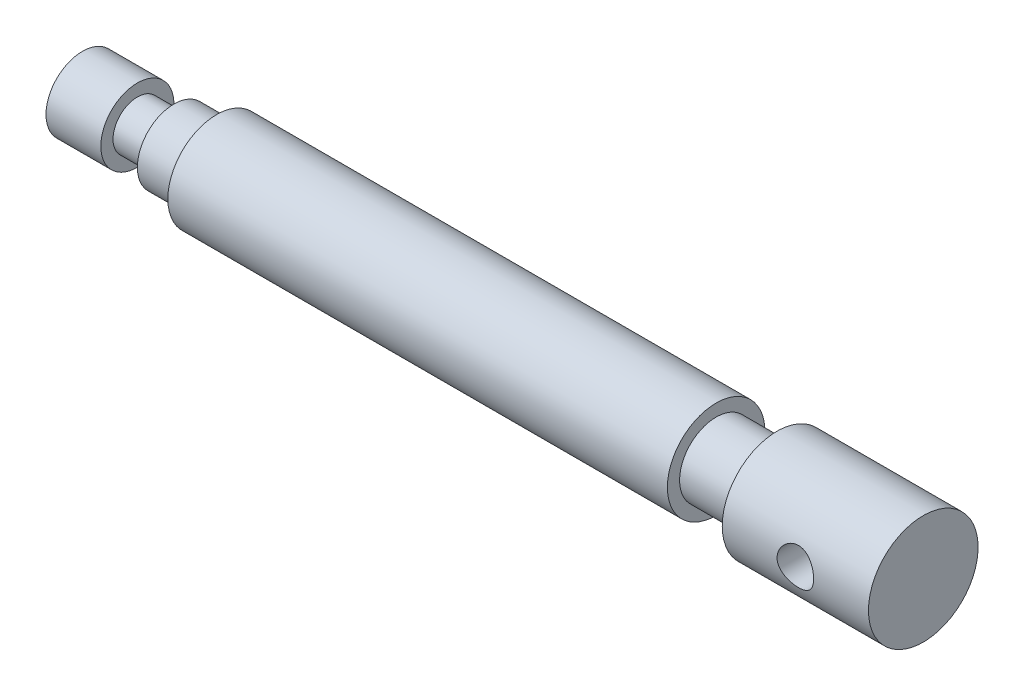
SolidWorks part; units mm, degrees
ref_plane "Front Plane" through (0, 0, 0) normal (0, 0, 1) x (1, 0, 0)
ref_plane "Top Plane" through (0, 0, 0) normal (0, 1, 0) x (1, 0, 0)
ref_plane "Right Plane" through (0, 0, 0) normal (1, 0, 0) x (0, 0, -1)
sketch "Sketch1" plane through (0, 0, 0) normal (0, 1, 0) x (1, 0, 0)
  line L0 (0, 0) -> (0, 22664.7318) construction
  line L1 (0, 0) -> (22664.7318, 0) construction
  line L2 (69, 0) -> (69, 9)
  line L3 (69, 9) -> (45, 9)
  line L4 (45, 9) -> (45, 6)
  line L5 (45, 6) -> (35, 6)
  line L6 (35, 6) -> (35, 8)
  line L7 (35, 8) -> (-47, 8)
  line L8 (-47, 8) -> (-47, 6)
  line L9 (-47, 6) -> (-54, 6)
  line L10 (-54, 6) -> (-54, 4)
  line L11 (-54, 4) -> (-60, 4)
  line L12 (-60, 4) -> (-60, 6)
  line L13 (-60, 6) -> (-69, 6)
  line L14 (-69, 6) -> (-69, 0)
  line L15 (-69, 0) -> (69, 0)
  point P19 (0, 0)
  dimension "D1" = 18
  dimension "D2" = 24
  dimension "D3" = 12
  dimension "D4" = 10
  dimension "D5" = 16
  dimension "D6" = 82
  dimension "D7" = 9
  dimension "D8" = 6
  dimension "D9" = 12
  dimension "D10" = 8
  dimension "D11" = 138
revolve "Revolve1" add sketch "Sketch1" angle 360 about L1
sketch "Sketch2" plane through (0, 0, 0) normal (0, 0, 1) x (1, 0, 0)
  line L0 (69, -9) -> (69, 9) construction
  circle A0 centre (57, 0) radius 3
  point P2 (0, 0)
  dimension "D1" = 6
  dimension "D2" = 12
extrude "Cut-Extrude1" cut sketch "Sketch2" against normal through all both and the other way through all
